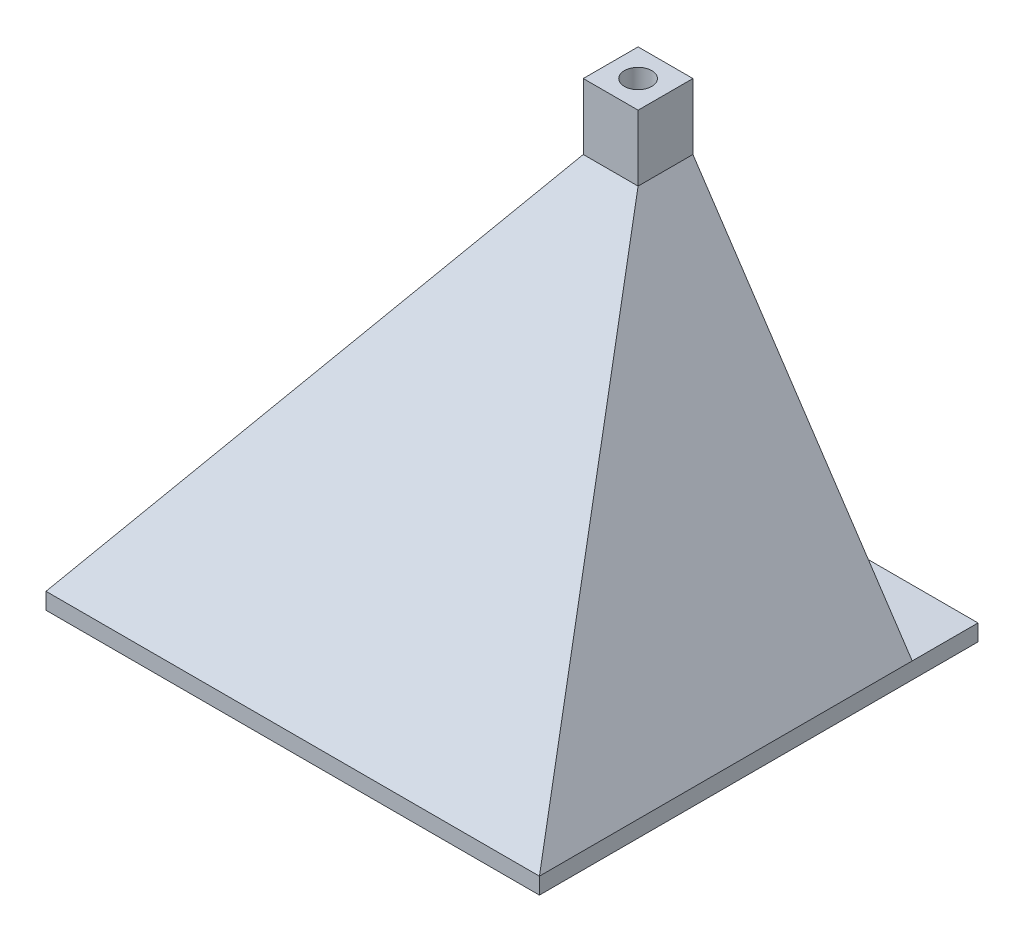
SolidWorks part; units mm, degrees
ref_plane "前视基准面" through (0, 0, 0) normal (0, 0, 1) x (1, 0, 0)
ref_plane "上视基准面" through (0, 0, 0) normal (0, 1, 0) x (1, 0, 0)
ref_plane "右视基准面" through (0, 0, 0) normal (1, 0, 0) x (0, 0, -1)
sketch "Sketch1" plane through (0, 0, 0) normal (0, 1, 0) x (1, 0, 0)
  line L0 (-22.5, 20) -> (22.5, -20) construction
  line L1 (0, 17) -> (0, 0) construction
  line L3 (-21.5, -19) -> (21.5, -19)
  line L4 (-21.5, -19) -> (-21.5, 13)
  line L5 (-21.5, 13) -> (21.5, 13)
  line L6 (21.5, -19) -> (21.5, 13)
  line L7 (-22.5, 20) -> (22.5, 20)
  line L8 (-22.5, 20) -> (-22.5, -20)
  line L9 (-22.5, -20) -> (22.5, -20)
  line L10 (22.5, 20) -> (22.5, -20)
  line L11 (-12.5, 17) -> (12.5, 17) construction
  line L12 (-12.5, 18.7) -> (12.5, 18.7)
  line L13 (-12.5, 15.3) -> (12.5, 15.3)
  arc A6 (-12.5, 18.7) -> (-12.5, 15.3) centre (-12.5, 17) ccw
  arc A7 (12.5, 15.3) -> (12.5, 18.7) centre (12.5, 17) ccw
  point P30 (0, 17)
  dimension "D6" = 1
  dimension "D7" = 1.7
  dimension "D1" = 1
  dimension "D2" = 1
  dimension "D3" = 45
  dimension "D4" = 40
  dimension "D5" = 7
  dimension "D8" = 25
  dimension "D9" = 3
extrude "Boss-Extrude1" add sketch "Sketch1" along normal blind 1.5
ref_plane "Plane1" through (0, 31.5, 0) normal (0, 1, 0) x (1, 0, 0)
sketch "Sketch5" plane through (0, 1.5, 0) normal (0, 1, 0) x (1, 0, 0)
  line L0 (22.5, -20) -> (22.5, 20) construction
  line L1 (-22.5, -20) -> (22.5, -20)
  line L2 (-22.5, -20) -> (-22.5, 14)
  line L3 (-22.5, 14) -> (22.5, 14)
  line L4 (22.5, -20) -> (22.5, 14)
  line L5 (22.5, 20) -> (-22.5, 20) construction
  dimension "D1" = 6
sketch "Sketch6" plane through (0, 31.5, 0) normal (0, 1, 0) x (1, 0, 0)
  line L0 (21.5, 13) -> (-21.5, 13) construction
  line L1 (0, 0) -> (0, 11.5) construction
  line L2 (-2.5, 9) -> (2.5, 9)
  line L3 (-2.5, 9) -> (-2.5, 14)
  line L4 (-2.5, 14) -> (2.5, 14)
  line L5 (2.5, 9) -> (2.5, 14)
  line L6 (-2.5, 9) -> (2.5, 14) construction
  line L8 (-2.5, 14) -> (2.5, 9) construction
  point P0 (0, 11.5)
  dimension "D1" = 5
  dimension "D2" = 1
loft "Loft3" add profiles "Sketch5", "Sketch6"
shell "Shell3" thickness 0.75
sketch "Sketch7" plane through (0, 31.5, 0) normal (0, 1, 0) x (1, 0, 0)
  line L0 (2.5, 9) -> (2.5, 14) construction
  line L1 (2.5, 14) -> (-2.5, 14) construction
  line L2 (-2.5, 14) -> (-2.5, 9) construction
  line L3 (-2.5, 9) -> (2.5, 9) construction
  line L4 (2.5, 14) -> (-2.5, 14)
  line L5 (-2.5, 14) -> (-2.5, 9)
  line L6 (-2.5, 9) -> (2.5, 9)
  line L7 (2.5, 9) -> (2.5, 14)
  line L8 (-2.5, 14) -> (2.5, 9) construction
  circle A0 centre (0, 11.5) radius 1.25
  dimension "D1" = 2.5
extrude "Boss-Extrude2" add sketch "Sketch7" along normal blind 6
sketch "Sketch8" plane through (0, 0, -14) normal (0, 0, -1) x (-1, 0, 0)
  line L0 (0, 37.5) -> (0, 14.5) construction
  line L1 (-2.5, 37.5) -> (2.5, 37.5) construction
  circle A0 centre (0, 14.5) radius 1.7
  dimension "D1" = 3.4
  dimension "D2" = 23
extrude "Cut-Extrude1" cut sketch "Sketch8" against normal up to next (0.75 mm away)
